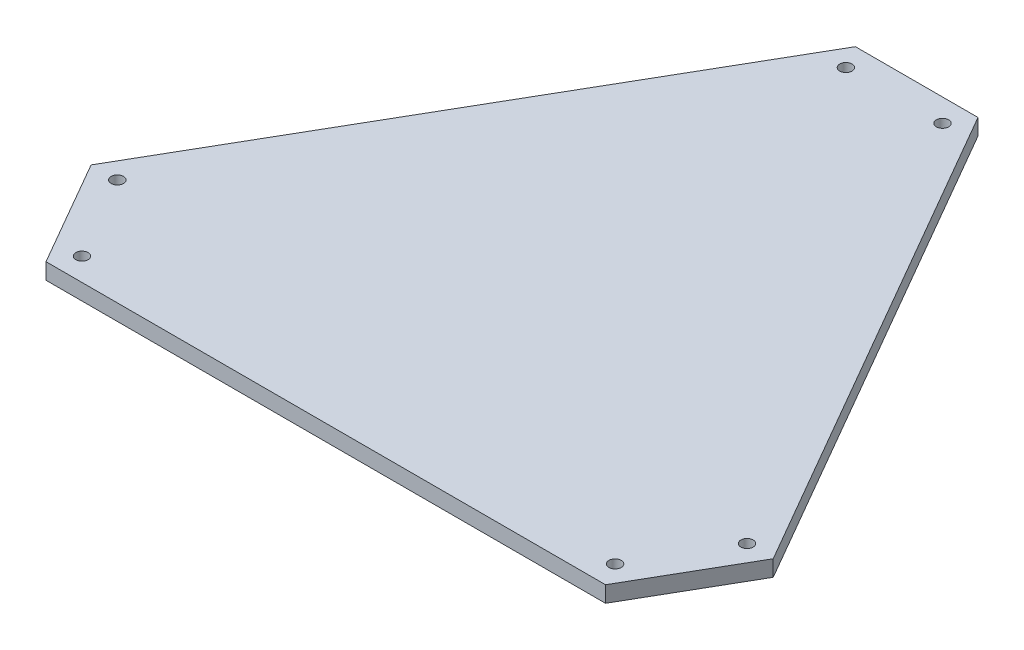
SolidWorks part; units mm, degrees
ref_plane "Plano frontal" through (0, 0, 0) normal (0, 0, 1) x (1, 0, 0)
ref_plane "Plano superior" through (0, 0, 0) normal (0, 1, 0) x (1, 0, 0)
ref_plane "Plano direito" through (0, 0, 0) normal (1, 0, 0) x (0, 0, -1)
sketch "Esboço1" plane through (0, 0, 0) normal (0, 1, 0) x (1, 0, 0)
  line L4 (0, 0) -> (0, 129.9) construction
  line L5 (-75, 0) -> (75, 0)
  line L8 (0, 129.9) -> (-75, 0)
  line L9 (0, 129.9) -> (75, 0)
  point P5 (0, 0)
  dimension "D1" = 129.9
  dimension "D2" = 150
extrude "Ressalto-extrusão1" add sketch "Esboço1" along normal blind 3
sketch "Esboço3" plane through (0, 3, 0) normal (0, 1, 0) x (1, 0, 0)
  line L0 (61.5924, 16.4133) -> (52.1282, 0) construction
  line L1 (-75, 0) -> (75, 0) construction
  line L2 (52.1282, 0) -> (63.5567, 19.8199)
  line L3 (75, 0) -> (0, 129.9) construction
  line L4 (63.5567, 19.8199) -> (75, 0)
  line L5 (75, 0) -> (52.1282, 0)
  line L6 (-61.6186, 16.4148) -> (-52.1412, 0) construction
  line L7 (-52.1412, 0) -> (-63.5567, 19.8199)
  line L8 (0, 129.9) -> (-75, 0) construction
  line L9 (-63.5567, 19.8199) -> (-75, 0)
  line L10 (-75, 0) -> (-52.1412, 0)
  line L11 (-11.4216, 110.1178) -> (11.4216, 110.1178)
  line L12 (11.4216, 110.1178) -> (0, 129.9)
  line L13 (0, 129.9) -> (-11.4216, 110.1178)
extrude "Corte-extrusão1" cut sketch "Esboço3" against normal through all
sketch "Esboço5" plane through (0, 3, 0) normal (0, 1, 0) x (1, 0, 0)
  line L6 (-52.1412, 0) -> (52.1282, 0)
  line L7 (52.1282, 0) -> (63.5567, 19.8199)
  line L8 (63.5567, 19.8199) -> (11.4216, 110.1178)
  line L9 (11.4216, 110.1178) -> (-11.4216, 110.1178)
  line L10 (-11.4216, 110.1178) -> (-63.5567, 19.8199)
  line L11 (-63.5567, 19.8199) -> (-52.1412, 0)
  line L12 (-52.1412, 0) -> (52.1282, 0)
  line L13 (52.1282, 0) -> (63.5567, 19.8199)
  line L14 (63.5567, 19.8199) -> (11.4216, 110.1178)
  line L15 (11.4216, 110.1178) -> (-11.4216, 110.1178)
  line L16 (-11.4216, 110.1178) -> (-63.5567, 19.8199)
  line L17 (-63.5567, 19.8199) -> (-52.1412, 0)
  circle A0 centre (-49.688, 4.2504) radius 1.15
  circle A1 centre (-58.688, 19.8388) radius 1.15
  circle A2 centre (58.6618, 19.8373) radius 1.15
  circle A3 centre (49.6618, 4.2489) radius 1.15
  circle A4 centre (-8.9435, 105.8658) radius 1.15
  circle A5 centre (9.0564, 105.8668) radius 1.15
  dimension "D1" = 0
extrude "Corte-extrusão3" cut sketch "Esboço5" against normal through all contours A0 | A1 | A3 | A2 | A4 | A5
